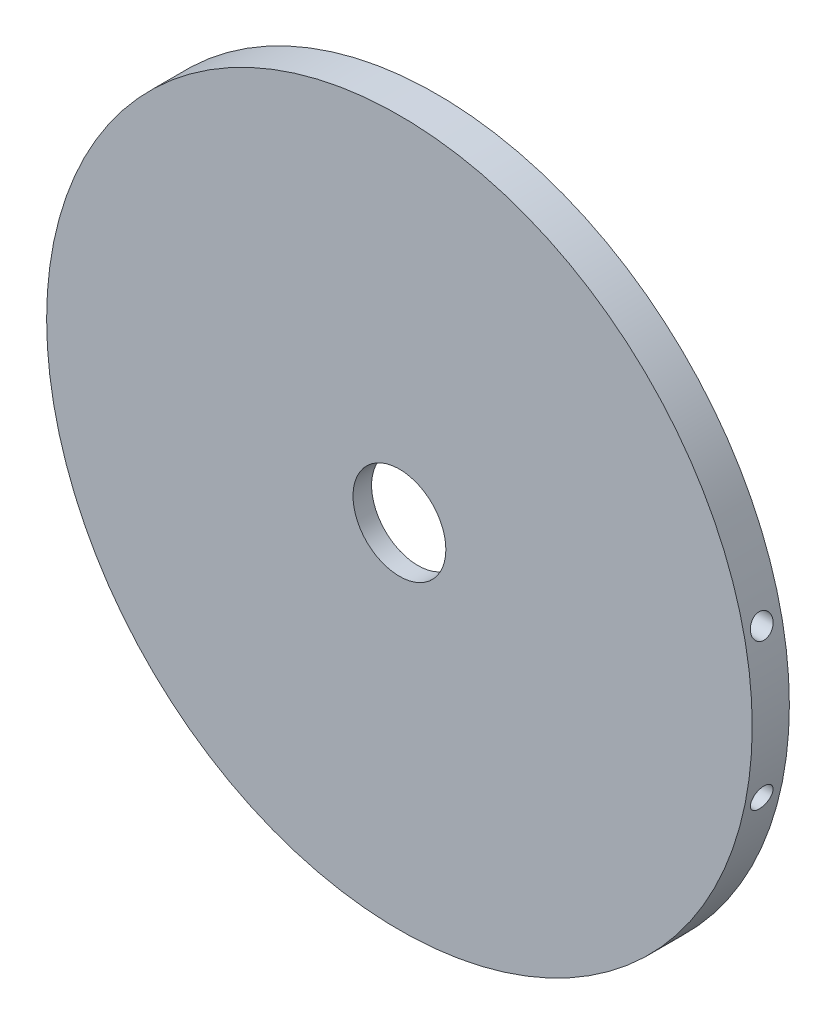
SolidWorks part; units mm, degrees
ref_plane "Front Plane" through (0, 0, 0) normal (0, 0, 1) x (1, 0, 0)
ref_plane "Top Plane" through (0, 0, 0) normal (0, 1, 0) x (1, 0, 0)
ref_plane "Right Plane" through (0, 0, 0) normal (1, 0, 0) x (0, 0, -1)
sketch "Sketch1" plane through (0, 0, 0) normal (0, 0, 1) x (1, 0, 0)
  circle A0 centre (0, 0) radius 19
  circle A1 centre (0, 0) radius 2.5
  circle A2 centre (0, 0) radius 7.5
  dimension "D1" = 38
  dimension "D2" = 5
  dimension "D3" = 15
extrude "Boss-Extrude5" add sketch "Sketch1" along normal blind 2 contours A0 A2 | A2 A1
sketch "Sketch10" plane through (0, 0, 0) normal (0, 0, 1) x (1, 0, 0)
  circle A0 centre (0, 0) radius 12
  dimension "D1" = 24
extrude "Cut-Extrude33" cut sketch "Sketch10" along normal blind 1
sketch "Sketch14" plane through (0, 0, 0) normal (1, 0, 0) x (0, 0, -1)
  circle A0 centre (-1.063, 4) radius 0.6
  circle A1 centre (-1.063, -4) radius 0.6
  dimension "D1" = 1.2
  dimension "D2" = 1.2
extrude "Cut-Extrude34" cut sketch "Sketch14" against normal blind 34 and the other way blind 40
